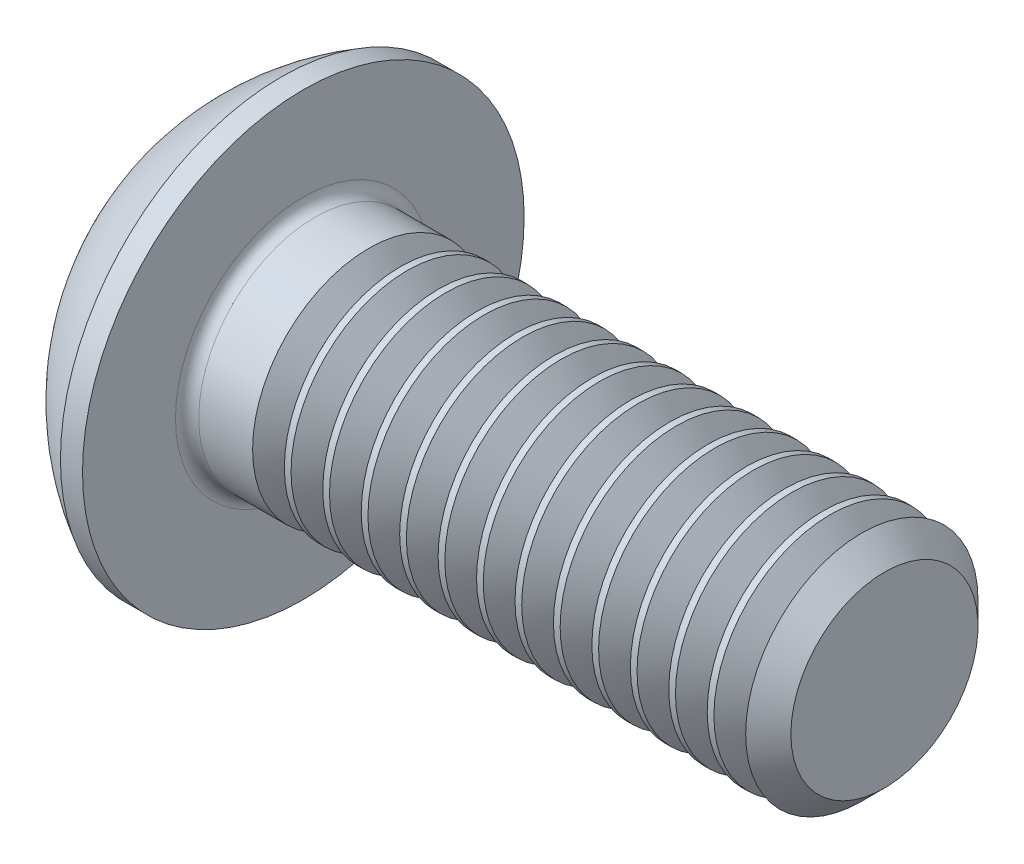
SolidWorks part; units mm, degrees
ref_plane "Plane1" through (0, 0, 0) normal (0, 0, 1) x (1, 0, 0)
ref_plane "Plane2" through (0, 0, 0) normal (0, 1, 0) x (1, 0, 0)
ref_plane "Plane3" through (0, 0, 0) normal (1, 0, 0) x (0, 0, -1)
sketch "BodySke" plane through (0, 0, 0) normal (0, 0, 1) x (1, 0, 0)
  line L0 (12.2, 0) -> (12.2, 1.61)
  line L1 (11.81, 2) -> (2.2, 2)
  line L2 (2.2, 2) -> (2.2, 3.8)
  line L3 (2.2, 3.8) -> (1.82, 3.8)
  line L4 (0, 0) -> (101.6, 0) construction
  line L5 (2.2, -3.8) -> (1.82, -3.8) construction
  line L6 (55.6768, -2) -> (2.2, -2) construction
  line L7 (12.2, 0) -> (0, 0)
  line L8 (0, 1.9) -> (0, -1.9) construction
  line L9 (0, 0) -> (0, 1.9)
  line L10 (12.2, 1.61) -> (11.81, 2)
  line L11 (12.2, -1.61) -> (11.81, -2) construction
  line L12 (2.9, 9.525) -> (2.9, -2) construction
  line L13 (2.2, 9.525) -> (2.2, -2) construction
  arc A1 (0, 1.9) -> (1.82, 3.8) centre (3.8853, 0) cw
  dimension "D1" = 3.8
  dimension "Diameter" = 4
  dimension "Length" = 10
  dimension "Head_dia" = 7.6
  dimension "Head_ht" = 2.2
  dimension "Head_side_ht" = 0.38
  dimension "Minor_dia" = 3.22
  dimension "Body_ch_ang" = 45
  dimension "Advance" = 0.7
  dimension "Thread_nom" = 10
revolve "BaseBody" add sketch "BodySke" angle 360 about L4
cosmetic thread "ThreadCosmetic" [suppressed] parameters "Thread_length"=8.6, "Thread_minor"=3.22
fillet "Fillet1" radius 0.2 1 edges at (2.2, 0, 2)
sketch "Sketch2" plane through (0, 0, 0) normal (0, 0, 1) x (1, 0, 0)
  line L0 (0, 1.25) -> (1.3, 1.25)
  line L1 (1.3, 1.25) -> (2.0217, 0)
  line L3 (2.0217, 0) -> (0, 0)
  line L4 (0, 0) -> (0, 1.25)
  line L5 (0, -1.25) -> (1.3, -1.25) construction
  line L6 (0, 0) -> (47.625, 0) construction
  dimension "D2" = 60
  dimension "PreBroach_depth" = 1.3
  dimension "PreBroach_dia" = 2.5
revolve "PreBroach" cut sketch "Sketch2" angle 360 about L6
sketch "Sketch3" plane through (0, 0, 0) normal (1, 0, 0) x (0, 0, -1)
  line L0 (-1.25, -0.7217) -> (-1.25, 0.7217)
  line L1 (-1.25, 0.7217) -> (0, 1.4434)
  line L2 (0, 1.4434) -> (1.25, 0.7217)
  line L3 (1.25, 0.7217) -> (1.25, -0.7217)
  line L4 (1.25, -0.7217) -> (0, -1.4434)
  line L5 (0, -1.4434) -> (-1.25, -0.7217)
  dimension "D1" = 1.25
  dimension "D2" = 1.25
  dimension "D3" = 2.5
  dimension "Hex_size" = 2.5
extrude "Hex" cut sketch "Sketch3" along normal blind 1.3
sketch "ThdSchSke" plane through (0, 0, 0) normal (0, 0, 1) x (1, 0, 0)
  line L0 (3.6, -1.61) -> (3.3269, -2)
  line L1 (3.6, -1.61) -> (3.8731, -2)
  line L2 (3.8731, -2) -> (3.8731, -2.5)
  line L3 (-3.175, 0) -> (5.1513, 0) construction
  line L5 (3.8731, -2.5) -> (3.3269, -2.5)
  line L6 (3.3269, -2.5) -> (3.3269, -2)
  dimension "Thread_minor" = 3.22
  dimension "Diameter" = 4
  dimension "Start" = 3.6
  dimension "SideAngle" = 55
  dimension "VeeAngle" = 70
  dimension "Overcut" = 5
revolve "ThreadSchematic" cut sketch "ThdSchSke" angle 360 about L3
pattern_linear "ThdSchPat" count 13 spacing 0.6615 along (1, 0, 0) of "ThreadSchematic"
equation "\"D1@BodySke\" = \"Head_dia@BodySke\" * .5"
equation "\"Thread_minor@ThreadCosmetic\" = \"Minor_dia@BodySke\""
equation "\"D1@Sketch3\" = \"Hex_size@Sketch3\" / 2"
equation "\"D2@Sketch3\" = \"D1@Sketch3\""
equation "\"D3@Sketch3\" = \"Hex_size@Sketch3\""
equation "\"Thread_length@ThreadCosmetic\" = ((sgn( (\"Length@BodySke\" - \"Advance@BodySke\" * 2.0) - \"Thread_nom@BodySke\" )-1)*( (\"Length@BodySke\" - \"Advance@BodySke\" * 2.0) - \"Thread_nom@BodySke\" ))/-2+ \"Thread_nom@BodySke\""
equation "\"Thread_minor@ThdSchSke\" = \"Minor_dia@BodySke\""
equation "\"Diameter@ThdSchSke\" = \"Diameter@BodySke\""
equation "\"Overcut@ThdSchSke\" = \"Diameter@BodySke\" * 1.25"
equation "\"Start@ThdSchSke\" = \"Head_ht@BodySke\" + \"Length@BodySke\" - \"Thread_length@ThreadCosmetic\"  '---Non-countersunk---"
equation "\"Num_threads@ThdSchPat\" = int( \"Thread_length@ThreadCosmetic\" / \"Advance@BodySke\" + 0.999 )  + 1"
equation "\"Advance@ThdSchPat\" = \"Thread_length@ThreadCosmetic\" /  (\"Num_threads@ThdSchPat\" - 1) 'relax it"
equation "\"Num_threads@ThdSchPat\" = \"Num_threads@ThdSchPat\" - sgn( \"Num_threads@ThdSchPat\" - 1) '---chamfered tips only---"
